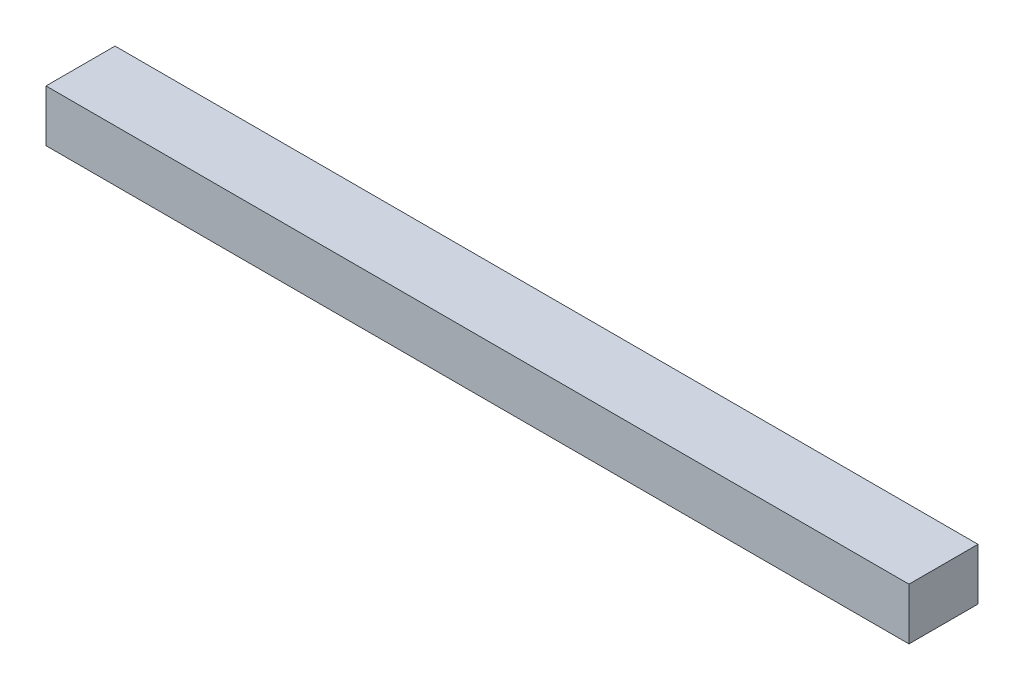
SolidWorks part; units mm, degrees
ref_plane "Front Plane" through (0, 0, 0) normal (0, 0, 1) x (1, 0, 0)
ref_plane "Top Plane" through (0, 0, 0) normal (0, 1, 0) x (1, 0, 0)
ref_plane "Right Plane" through (0, 0, 0) normal (1, 0, 0) x (0, 0, -1)
sketch "Sketch1" plane through (0, 0, 0) normal (0, 1, 0) x (1, 0, 0)
  line L1 (0, 0) -> (-50, 0)
  line L2 (0, 0) -> (0, 4)
  line L3 (0, 4) -> (-50, 4)
  line L4 (-50, 0) -> (-50, 4)
  dimension "D1" = 4
  dimension "D2" = 50
extrude "Boss-Extrude1" add sketch "Sketch1" along normal blind 3
